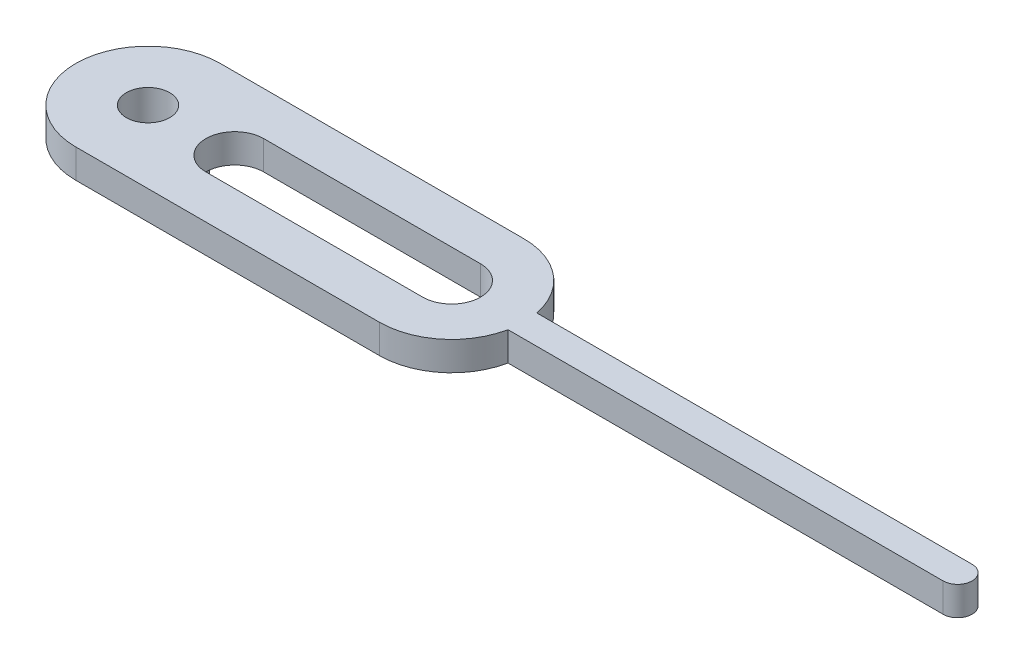
SolidWorks part; units mm, degrees
ref_plane "Front Plane" through (0, 0, 0) normal (0, 0, 1) x (1, 0, 0)
ref_plane "Top Plane" through (0, 0, 0) normal (0, 1, 0) x (1, 0, 0)
ref_plane "Right Plane" through (0, 0, 0) normal (1, 0, 0) x (0, 0, -1)
sketch "Sketch1" plane through (0, 0, 0) normal (0, 1, 0) x (1, 0, 0)
  line L0 (-115, 0) -> (115, 0) construction
  line L1 (-115, 25) -> (115, 25) construction
  line L2 (-115, -25) -> (115, -25) construction
  line L3 (-85, 0) -> (115, 0) construction
  line L4 (-85, 10) -> (115, 10) construction
  line L5 (-85, -10) -> (115, -10) construction
  line L6 (-10, 10) -> (-85, 10)
  line L7 (-85, -10) -> (-10, -10)
  line L8 (-115, -25) -> (-10, -25)
  line L9 (-10, 25) -> (-115, 25)
  line L10 (14.4949, 5) -> (165, 5)
  line L11 (165, -5) -> (14.4949, -5)
  arc A0 (-115, 25) -> (-115, -25) centre (-115, 0) ccw construction
  arc A1 (115, -25) -> (115, 25) centre (115, 0) ccw construction
  arc A2 (-85, 10) -> (-85, -10) centre (-85, 0) ccw construction
  arc A3 (115, -10) -> (115, 10) centre (115, 0) ccw construction
  circle A4 centre (-115, 0) radius 7.5
  arc A5 (-10, 10) -> (-10, -10) centre (-10, 0) cw
  arc A6 (-85, 10) -> (-85, -10) centre (-85, 0) ccw
  arc A7 (-115, 25) -> (-115, -25) centre (-115, 0) ccw
  arc A8 (-10, -25) -> (14.4949, -5) centre (-10, 0) ccw
  arc A9 (165, 5) -> (165, -5) centre (165, 0) cw
  arc A10 (14.4949, 5) -> (-10, 25) centre (-10, 0) ccw
  point P2 (0, 0)
  point P9 (15, 0)
  point P31 (0, 0)
  point P35 (0, 0)
  point P36 (0, 0)
  point P37 (0, 0)
  dimension "D3" = 15
  dimension "D1" = 50
  dimension "D2" = 230
  dimension "D4" = 200
  dimension "D5" = 20
  dimension "D6" = 10
  dimension "D7" = 5
  dimension "D8" = 150
extrude "Boss-Extrude1" add sketch "Sketch1" along normal blind 10 contours L10 A10 L9 A7 L8 A8 L11 A9 A4 A6 L6 A5 L7
sketch "Sketch2" plane through (0, 0, 0) normal (0, -1, 0) x (1, 0, 0)
  circle A0 centre (-115, 0) radius 15
  circle A1 centre (-115, 0) radius 7.5 construction
  circle A2 centre (-115, 0) radius 7.5
  dimension "D1" = 30
extrude "Boss-Extrude2" add sketch "Sketch2" along normal blind 10
